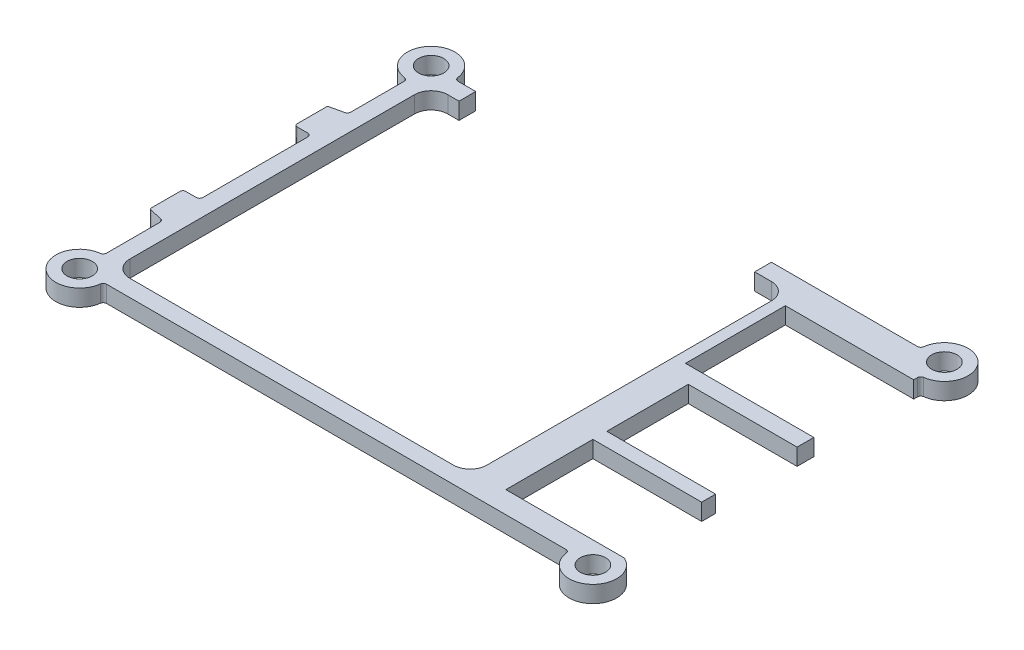
SolidWorks part; units mm, degrees
material "Balsa"
ref_plane "Front Plane" through (0, 0, 0) normal (0, 0, 1) x (1, 0, 0)
ref_plane "Top Plane" through (0, 0, 0) normal (0, 1, 0) x (1, 0, 0)
ref_plane "Right Plane" through (0, 0, 0) normal (1, 0, 0) x (0, 0, -1)
sketch "Sketch1" plane through (0, 0, 0) normal (0, 1, 0) x (1, 0, 0)
  line L0 (46, 0) -> (46, -63) construction
  line L5 (4.265, 0) -> (87.735, 0)
  line L6 (3.2, -3.25) -> (88.8, -3.25) construction
  line L7 (3.2, -3.25) -> (3.2, -59.75) construction
  line L8 (3.2, -59.75) -> (88.8, -59.75) construction
  line L9 (88.8, -3.25) -> (88.8, -59.75) construction
  line L10 (3.2, -3.25) -> (88.8, -59.75) construction
  line L11 (3.2, -59.75) -> (88.8, -3.25) construction
  line L12 (0, -4.265) -> (0, -58.735)
  line L14 (92, -4.265) -> (92, -58.735)
  line L15 (4.265, -63) -> (87.735, -63)
  circle A0 centre (0, 0) radius 2.265
  circle A1 centre (92, 0) radius 2.265
  circle A2 centre (92, -63) radius 2.265
  circle A3 centre (0, -63) radius 2.265
  arc A4 (4.265, 0) -> (0, -4.265) centre (0, 0) ccw
  arc A5 (92, -4.265) -> (87.735, 0) centre (92, 0) ccw
  arc A6 (87.735, -63) -> (92, -58.735) centre (92, -63) ccw
  arc A7 (0, -58.735) -> (4.265, -63) centre (0, -63) ccw
  point P7 (46, -31.5)
  dimension "D5" = 4.53
  dimension "D6" = 2
  dimension "D1" = 92
  dimension "D2" = 63
  dimension "D3" = 85.6
  dimension "D4" = 56.5
extrude "Boss-Extrude1" add sketch "Sketch1" along normal blind 3
sketch "Sketch2" plane through (0, 3, 0) normal (0, 1, 0) x (1, 0, 0)
  line L0 (0, -31.5) -> (92, -31.5) construction
  line L1 (0, -4.265) -> (0, -58.735) construction
  line L2 (92, -58.735) -> (92, -4.265) construction
  line L4 (0, -21.5) -> (6.5, -21.5)
  line L5 (0, -21.5) -> (0, -41.5)
  line L6 (0, -41.5) -> (6.5, -41.5)
  line L7 (6.5, -21.5) -> (6.5, -41.5)
  point P11 (0, -31.5)
  dimension "D1" = 20
  dimension "D2" = 6.5
extrude "Cut-Extrude1" cut sketch "Sketch2" against normal blind 3
sketch "Sketch3" plane through (0, 3, 0) normal (0, 1, 0) x (1, 0, 0)
  line L0 (-2.7, -15.5) -> (0, -14.9)
  line L1 (0, -21.5) -> (-2.5, -21.5)
  line L2 (0, -21.5) -> (0, -14.9)
  line L4 (-3, -21) -> (-3, -15.8)
  line L5 (6.5, -31.5) -> (-19.974, -31.5) construction
  line L6 (6.5, -41.5) -> (6.5, -21.5) construction
  line L7 (-3, -42) -> (-3, -47.2)
  line L8 (0, -41.5) -> (-2.5, -41.5)
  line L9 (0, -41.5) -> (0, -48.1)
  line L10 (-2.7, -47.5) -> (0, -48.1)
  arc A0 (-3, -21) -> (-2.5, -21.5) centre (-2.5, -21) ccw
  arc A1 (-3, -15.8) -> (-2.7, -15.5) centre (-2.7, -15.8) cw
  arc A2 (-3, -47.2) -> (-2.7, -47.5) centre (-2.7, -47.2) ccw
  arc A3 (-3, -42) -> (-2.5, -41.5) centre (-2.5, -42) cw
  point P7 (-3, -21.5)
  point P10 (-3, -15.5)
  dimension "D3" = 0.5
  dimension "D4" = 0.3
  dimension "D1" = 3
  dimension "D2" = 6
  dimension "D5" = 6.6
extrude "Boss-Extrude2" add sketch "Sketch3" against normal blind 3
sketch "Sketch4" plane through (0, 3, 0) normal (0, 1, 0) x (1, 0, 0)
  line L0 (0, -4.265) -> (0, -14.9) construction
  line L1 (6, -3) -> (64, -3)
  line L2 (3, -6) -> (3, -57)
  line L3 (6, -60) -> (64, -60)
  line L4 (67, -6) -> (67, -57)
  line L6 (4.265, -63) -> (87.735, -63) construction
  line L7 (87.735, 0) -> (4.265, 0) construction
  arc A0 (6, -60) -> (3, -57) centre (6, -57) cw
  arc A1 (67, -57) -> (64, -60) centre (64, -57) cw
  arc A2 (67, -6) -> (64, -3) centre (64, -6) ccw
  arc A3 (3, -6) -> (6, -3) centre (6, -6) cw
  dimension "D5" = 3
  dimension "D1" = 3
  dimension "D2" = 3
  dimension "D3" = 3
  dimension "D4" = 67
extrude "Cut-Extrude2" cut sketch "Sketch4" against normal blind 3
sketch "Sketch5" plane through (0, 3, 0) normal (0, 1, 0) x (1, 0, 0)
  line L0 (-2.5, -41.5) -> (3, -41.5) construction
  line L1 (3, -21.5) -> (0, -21.5)
  line L2 (3, -21.5) -> (3, -41.5)
  line L3 (3, -41.5) -> (0, -41.5)
  line L4 (0, -21.5) -> (0, -41.5)
extrude "Boss-Extrude3" add sketch "Sketch5" against normal blind 3
sketch "Sketch6" plane through (0, 3, 0) normal (0, 1, 0) x (1, 0, 0)
  line L0 (67, -57) -> (67, -6) construction
  line L1 (69, -5.5) -> (96.0101, -5.5)
  line L2 (69, -5.5) -> (69, -23.4)
  line L3 (69, -23.4) -> (96.0101, -23.4)
  line L4 (96.0101, -5.5) -> (96.0101, -23.4)
  line L5 (87.735, 0) -> (4.265, 0) construction
  dimension "D1" = 2
  dimension "D2" = 17.9
  dimension "D3" = 5.5
extrude "Cut-Extrude3" cut sketch "Sketch6" against normal blind 3
sketch "Sketch7" plane through (0, 3, 0) normal (0, 1, 0) x (1, 0, 0)
  line L0 (92, -58.735) -> (92, -23.4) construction
  line L1 (72.5, -26.4) -> (92, -26.4)
  line L2 (72.5, -26.4) -> (72.5, -41)
  line L3 (72.5, -41) -> (92, -41)
  line L4 (92, -26.4) -> (92, -41)
  line L5 (69, -23.4) -> (92, -23.4) construction
  line L6 (67, -57) -> (67, -6) construction
  line L7 (4.265, -63) -> (87.735, -63) construction
  dimension "D1" = 3
  dimension "D2" = 5.5
  dimension "D3" = 22
extrude "Cut-Extrude4" cut sketch "Sketch7" against normal blind 3
sketch "Sketch8" plane through (0, 3, 0) normal (0, 1, 0) x (1, 0, 0)
  line L0 (92, -58.735) -> (92, -41) construction
  line L1 (72.5, -43.5) -> (92, -43.5)
  line L2 (72.5, -43.5) -> (72.5, -59.1)
  line L3 (72.5, -59.1) -> (92, -59.1)
  line L4 (92, -43.5) -> (92, -59.1)
  line L5 (72.5, -41) -> (92, -41) construction
  line L6 (67, -57) -> (67, -6) construction
  line L7 (4.265, -63) -> (87.735, -63) construction
  dimension "D1" = 2.5
  dimension "D2" = 5.5
  dimension "D3" = 3.9
extrude "Cut-Extrude5" cut sketch "Sketch8" against normal blind 3
sketch "Sketch9" plane through (0, 3, 0) normal (0, 1, 0) x (1, 0, 0)
  line L1 (92, -59.1) -> (94.0196, -59.1)
  line L2 (92, -59.1) -> (92, -58.5257)
  line L3 (92, -58.5257) -> (94.0196, -58.5257)
  line L4 (94.0196, -59.1) -> (94.0196, -58.5257)
extrude "Cut-Extrude6" cut sketch "Sketch9" against normal blind 3
fillet "Fillet1" radius 0.6 12 edges at (87.735, 1.5, 0) (92, 1.5, 4.265) (93.7263, 1.5, 59.1) (87.735, 1.5, 63) (4.265, 1.5, 63) (0, 1.5, 58.735) (0, 1.5, 48.1) (0, 1.5, 41.5) (4.265, 1.5, 0) (0, 1.5, 14.9) (0, 1.5, 4.265) (0, 1.5, 21.5)
sketch "Sketch10" plane through (0, 3, 0) normal (0, 1, 0) x (1, 0, 0)
  line L0 (87.1721, 0) -> (4.8279, 0) construction
  line L1 (8, 0) -> (61, 0)
  line L2 (8, 0) -> (8, -3)
  line L3 (8, -3) -> (61, -3)
  line L4 (61, 0) -> (61, -3)
  line L5 (64, -3) -> (6, -3) construction
  line L6 (3, -6) -> (3, -57) construction
  line L7 (67, -57) -> (67, -6) construction
  dimension "D1" = 5
  dimension "D2" = 6
extrude "Cut-Extrude7" cut sketch "Sketch10" against normal blind 10
